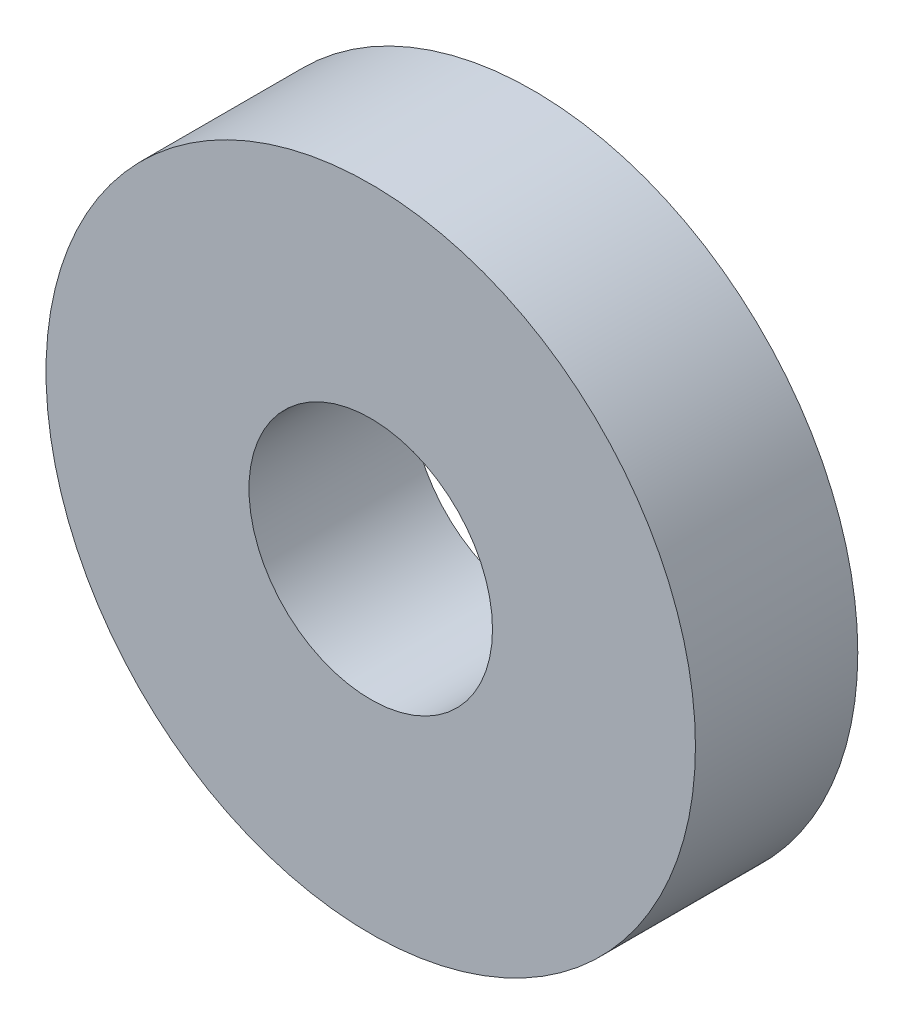
SolidWorks part; units mm, degrees
ref_plane "前视基准面" through (0, 0, 0) normal (0, 0, 1) x (1, 0, 0)
ref_plane "上视基准面" through (0, 0, 0) normal (0, 1, 0) x (1, 0, 0)
ref_plane "右视基准面" through (0, 0, 0) normal (1, 0, 0) x (0, 0, -1)
other "Configuration Table"
sketch "草图1" plane through (0, 0, 0) normal (0, 0, 1) x (1, 0, 0)
  circle A0 centre (0, 0) radius 20
  circle A1 centre (0, 0) radius 7.5
  dimension "D1" = 40
  dimension "D2" = 15
extrude "凸台-拉伸1" add sketch "草图1" along normal mid plane 10
